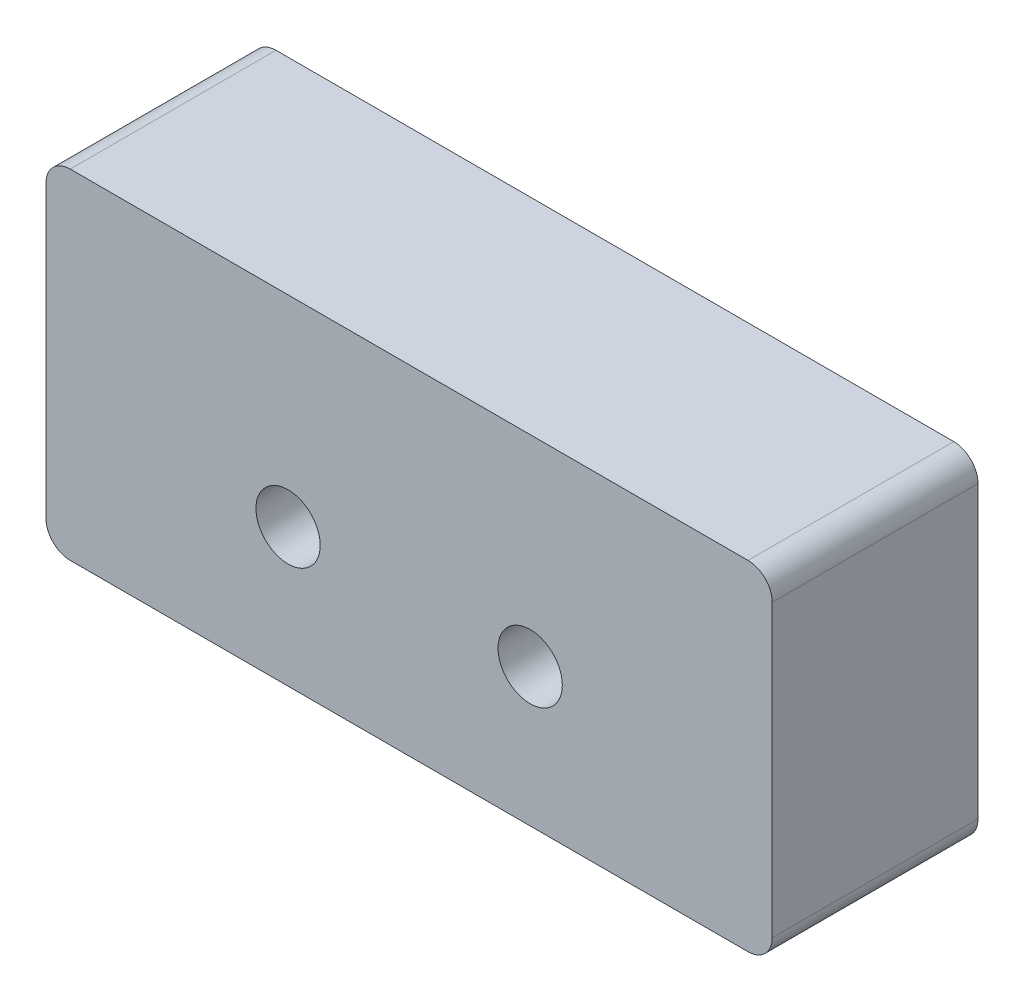
SolidWorks part; units mm, degrees
ref_plane "Front Plane" through (0, 0, 0) normal (0, 0, 1) x (1, 0, 0)
ref_plane "Top Plane" through (0, 0, 0) normal (0, 1, 0) x (1, 0, 0)
ref_plane "Right Plane" through (0, 0, 0) normal (1, 0, 0) x (0, 0, -1)
sketch "Sketch1" plane through (0, 0, 0) normal (0, 0, 1) x (1, 0, 0)
  line L0 (0, 0) -> (0, 35.56)
  line L1 (0, 35.56) -> (76.2, 35.56)
  line L2 (76.2, 35.56) -> (76.2, 0)
  line L3 (76.2, 0) -> (0, 0)
  line L5 (38.1, 35.56) -> (38.1, 0) construction
  circle A0 centre (25.4, 14.478) radius 3.3734
  circle A1 centre (50.8, 14.478) radius 3.3734
  dimension "D3" = 6.7469
  dimension "D1" = 76.2
  dimension "D2" = 35.56
  dimension "D5" = 12.7
  dimension "D6" = 12.7
  dimension "D7" = 14.478
extrude "Boss-Extrude1" add sketch "Sketch1" along normal blind 21.59
fillet "Fillet1" radius 2.54 4 edges at (76.2, 0, 10.795) (0, 0, 10.795) (76.2, 35.56, 10.795) (0, 35.56, 10.795)
sketch "Sketch2" plane through (0, 35.56, 0) normal (0, 1, 0) x (1, 0, 0)
  line L0 (2.54, -10.795) -> (73.66, -10.795) construction
  line L1 (2.54, 0) -> (2.54, -21.59) construction
  line L2 (73.66, -21.59) -> (73.66, 0) construction
  line L4 (76.2, 0) -> (76.2, -21.59) construction
  point P6 (63.5, -10.795)
  dimension "D1" = 12.7
equation "\"D3@Sketch1\"=\"D4@Sketch1\""
